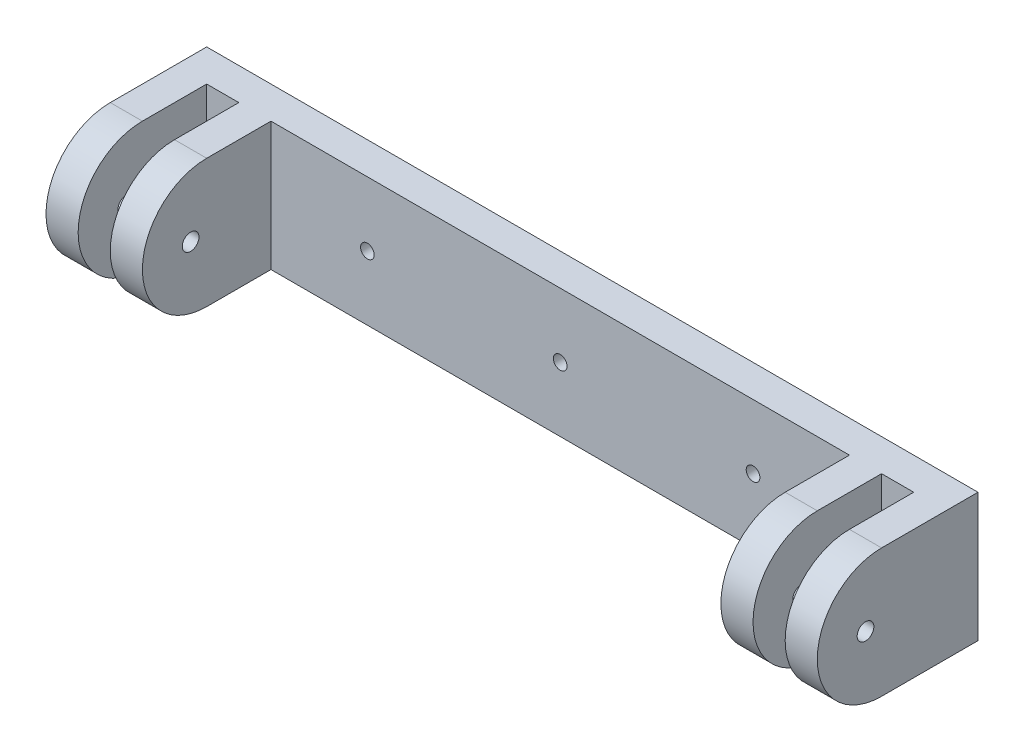
SolidWorks part; units mm, degrees
ref_plane "Front Plane" through (0, 0, 0) normal (0, 0, 1) x (1, 0, 0)
ref_plane "Top Plane" through (0, 0, 0) normal (0, 1, 0) x (1, 0, 0)
ref_plane "Right Plane" through (0, 0, 0) normal (1, 0, 0) x (0, 0, -1)
sketch "Sketch1" plane through (0, 0, 0) normal (0, 0, 1) x (1, 0, 0)
  line L1 (0, 0) -> (240, 0)
  line L2 (0, 0) -> (0, 40)
  line L3 (0, 40) -> (240, 40)
  line L4 (240, 0) -> (240, 40)
  dimension "D1" = 240
  dimension "D2" = 40
extrude "Boss-Extrude1" add sketch "Sketch1" along normal blind 10
sketch "Sketch2" plane through (240, 0, 0) normal (1, 0, 0) x (0, 0, -1)
  line L1 (-10, 40) -> (-30, 40)
  line L2 (-10, 40) -> (-10, 0)
  line L3 (-10, 0) -> (-30, 0)
  line L4 (-30, 40) -> (-30, 0)
  arc A0 (-30, 40) -> (-30, 0) centre (-30, 20) ccw
  line M3 (-10, 40) -> (-10, 0)
  dimension "D1" = 20
  dimension "D2" = 40
extrude "Boss-Extrude2" add sketch "Sketch2" against normal up to surface (240 mm away) contours L1 L4 L3 M3 | L4 A0 up to face at (0, 20, 5)
sketch "Sketch3" plane through (240, 0, 0) normal (1, 0, 0) x (0, 0, -1)
  line L0 (0, 0) -> (0, 40) construction
  line L1 (-30, 40) -> (0, 40) construction
  circle A0 centre (-35, 20) radius 2.6
  dimension "D2" = 5.2
  dimension "D1" = 35
  dimension "D3" = 20
extrude "Cut-Extrude1" cut sketch "Sketch3" against normal blind 300
sketch "Sketch4" plane through (0, 0, 0) normal (0, -1, 0) x (1, 0, 0)
  line L0 (240, 50) -> (0, 50) construction
  line L1 (10, 10) -> (20, 10)
  line L2 (10, 10) -> (10, 50)
  line L3 (10, 50) -> (20, 50)
  line L4 (20, 10) -> (20, 50)
  line L5 (0, 0) -> (240, 0) construction
  line L6 (30, 50) -> (210, 50)
  line L7 (30, 50) -> (30, 10)
  line L8 (30, 10) -> (210, 10)
  line L9 (210, 50) -> (210, 10)
  line L10 (220, 50) -> (230, 50)
  line L11 (220, 50) -> (220, 10)
  line L12 (220, 10) -> (230, 10)
  line L13 (230, 50) -> (230, 10)
  line L14 (240, 30) -> (240, 50) construction
  line L15 (0, 50) -> (0, 30) construction
  dimension "D1" = 10
  dimension "D2" = 10
  dimension "D3" = 10
  dimension "D4" = 10
  dimension "D5" = 10
  dimension "D6" = 10
  dimension "D7" = 10
extrude "Cut-Extrude2" cut sketch "Sketch4" against normal blind 300
sketch "Sketch5" plane through (0, 0, 0) normal (0, 0, -1) x (-1, 0, 0)
  line L0 (-240, 0) -> (-240, 40) construction
  line L2 (0, 0) -> (-240, 0) construction
  circle A0 centre (-180, 20) radius 2.125
  circle A1 centre (-120, 20) radius 2.125
  circle A2 centre (-60, 20) radius 2.125
  dimension "D1" = 4.25
  dimension "D2" = 4.25
  dimension "D3" = 4.25
  dimension "D4" = 60
  dimension "D5" = 60
  dimension "D6" = 60
  dimension "D7" = 20
extrude "Cut-Extrude3" cut sketch "Sketch5" against normal blind 300
